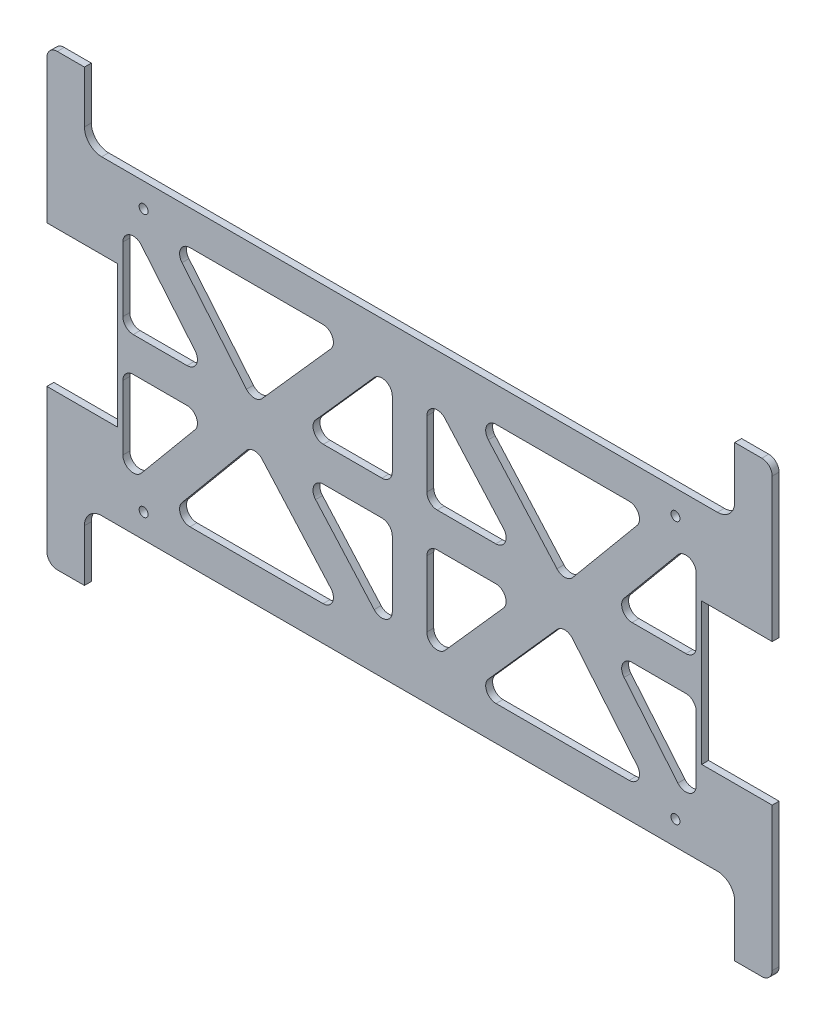
SolidWorks part; units mm, degrees
ref_plane "前视基准面" through (0, 0, 0) normal (0, 0, 1) x (1, 0, 0)
ref_plane "上视基准面" through (0, 0, 0) normal (0, 1, 0) x (1, 0, 0)
ref_plane "右视基准面" through (0, 0, 0) normal (1, 0, 0) x (0, 0, -1)
sketch "草图1" plane through (0, 0, 0) normal (0, 0, 1) x (1, 0, 0)
  line L0 (105, 90) -> (105, -49910) construction
  line L1 (7.8, 0) -> (202.2, 0)
  line L2 (0, 0) -> (0, 90)
  line L3 (7.8, 90) -> (202.2, 90)
  line L4 (210, 0) -> (210, 90)
  line L5 (0, 45) -> (210, 45) construction
  line L6 (10, 48.9878) -> (10, -49951.0122) construction
  line L7 (205.2, 93) -> (205.2, 110)
  line L8 (3, -20) -> (4.8, -20)
  line L9 (0, 90) -> (0, 107)
  line L10 (3, 110) -> (4.8, 110)
  line L11 (4.8, 93) -> (4.8, 110)
  line L12 (207, 110) -> (205.2, 110)
  line L13 (210, 90) -> (210, 107)
  line L14 (22, 71.7103) -> (22, 53)
  line L15 (207, -20) -> (205.2, -20)
  line L16 (210, 0) -> (210, -17)
  line L17 (205.2, -3) -> (205.2, -20)
  line L18 (4.8, -3) -> (4.8, -20)
  line L19 (0, 0) -> (0, -17)
  line L20 (25, 50) -> (40.5831, 50)
  line L21 (42.8883, 54.9199) -> (27.3052, 73.6302)
  line L22 (39.1117, 75.0801) -> (57.7672, 52.6808)
  line L23 (62.316, 52.6093) -> (82.1982, 75.0085)
  line L24 (79.9546, 80) -> (41.4169, 80)
  line L25 (100, 72.101) -> (100, 53)
  line L26 (97, 50) -> (80.0454, 50)
  line L27 (77.8018, 54.9915) -> (94.7564, 74.0925)
  line L28 (113, 50) -> (129.9546, 50)
  line L29 (110, 72.101) -> (110, 53)
  line L30 (132.1982, 54.9915) -> (115.2436, 74.0925)
  line L31 (147.684, 52.6093) -> (127.8018, 75.0085)
  line L32 (130.0454, 80) -> (168.5831, 80)
  line L33 (170.8883, 75.0801) -> (152.2328, 52.6808)
  line L34 (167.1117, 54.9199) -> (182.6948, 73.6302)
  line L35 (185, 50) -> (169.4169, 50)
  line L36 (188, 71.7103) -> (188, 53)
  line L37 (185, 40) -> (169.4169, 40)
  line L38 (188, 18.2897) -> (188, 37)
  line L39 (167.1117, 35.0801) -> (182.6948, 16.3698)
  line L40 (170.8883, 14.9199) -> (152.2328, 37.3192)
  line L41 (130.0454, 10) -> (168.5831, 10)
  line L42 (147.684, 37.3907) -> (127.8018, 14.9915)
  line L43 (113, 40) -> (129.9546, 40)
  line L44 (110, 17.899) -> (110, 37)
  line L45 (132.1982, 35.0085) -> (115.2436, 15.9075)
  line L46 (97, 40) -> (80.0454, 40)
  line L47 (100, 17.899) -> (100, 37)
  line L48 (77.8018, 35.0085) -> (94.7564, 15.9075)
  line L49 (62.316, 37.3907) -> (82.1982, 14.9915)
  line L50 (79.9546, 10) -> (41.4169, 10)
  line L51 (39.1117, 14.9199) -> (57.7672, 37.3192)
  line L52 (42.8883, 35.0801) -> (27.3052, 16.3698)
  line L53 (25, 40) -> (40.5831, 40)
  line L54 (22, 18.2897) -> (22, 37)
  circle A0 centre (2.5, 53) radius 1.75
  circle A1 centre (17.5, 53) radius 1.75
  circle A2 centre (17.5, 37) radius 1.75
  circle A3 centre (2.5, 37) radius 1.75
  circle A4 centre (207.5, 37) radius 1.75
  circle A5 centre (192.5, 37) radius 1.75
  circle A6 centre (192.5, 53) radius 1.75
  circle A7 centre (207.5, 53) radius 1.75
  arc A8 (205.2, 93) -> (202.2, 90) centre (202.2, 93) cw
  arc A9 (7.8, 90) -> (4.8, 93) centre (7.8, 93) cw
  arc A10 (4.8, -3) -> (7.8, 0) centre (7.8, -3) cw
  arc A11 (205.2, -3) -> (202.2, 0) centre (202.2, -3) ccw
  arc A12 (185, 50) -> (188, 53) centre (185, 53) ccw
  arc A13 (167.1117, 54.9199) -> (169.4169, 50) centre (169.4169, 53) ccw
  arc A14 (182.6948, 73.6302) -> (188, 71.7103) centre (185, 71.7103) cw
  arc A15 (168.5831, 80) -> (170.8883, 75.0801) centre (168.5831, 77) cw
  arc A16 (127.8018, 75.0085) -> (130.0454, 80) centre (130.0454, 77) cw
  arc A17 (113, 50) -> (110, 53) centre (113, 53) cw
  arc A18 (110, 72.101) -> (115.2436, 74.0925) centre (113, 72.101) cw
  arc A19 (129.9546, 50) -> (132.1982, 54.9915) centre (129.9546, 53) ccw
  arc A20 (169.4169, 40) -> (167.1117, 35.0801) centre (169.4169, 37) ccw
  arc A21 (185, 40) -> (188, 37) centre (185, 37) cw
  arc A22 (188, 18.2897) -> (182.6948, 16.3698) centre (185, 18.2897) cw
  arc A23 (170.8883, 14.9199) -> (168.5831, 10) centre (168.5831, 13) cw
  arc A24 (130.0454, 10) -> (127.8018, 14.9915) centre (130.0454, 13) cw
  arc A25 (152.2328, 37.3192) -> (147.684, 37.3907) centre (149.9276, 35.3992) ccw
  arc A26 (129.9546, 40) -> (132.1982, 35.0085) centre (129.9546, 37) cw
  arc A27 (113, 40) -> (110, 37) centre (113, 37) ccw
  arc A28 (110, 17.899) -> (115.2436, 15.9075) centre (113, 17.899) ccw
  arc A29 (82.1982, 14.9915) -> (79.9546, 10) centre (79.9546, 13) cw
  arc A30 (100, 17.899) -> (94.7564, 15.9075) centre (97, 17.899) cw
  arc A31 (80.0454, 40) -> (77.8018, 35.0085) centre (80.0454, 37) ccw
  arc A32 (97, 40) -> (100, 37) centre (97, 37) cw
  arc A33 (100, 53) -> (97, 50) centre (97, 53) cw
  arc A34 (100, 72.101) -> (94.7564, 74.0925) centre (97, 72.101) ccw
  arc A35 (80.0454, 50) -> (77.8018, 54.9915) centre (80.0454, 53) cw
  arc A36 (57.7672, 52.6808) -> (62.316, 52.6093) centre (60.0724, 54.6008) ccw
  arc A37 (62.316, 37.3907) -> (57.7672, 37.3192) centre (60.0724, 35.3992) ccw
  arc A38 (41.4169, 10) -> (39.1117, 14.9199) centre (41.4169, 13) cw
  arc A39 (27.3052, 16.3698) -> (22, 18.2897) centre (25, 18.2897) cw
  arc A40 (25, 40) -> (22, 37) centre (25, 37) ccw
  arc A41 (42.8883, 35.0801) -> (40.5831, 40) centre (40.5831, 37) ccw
  arc A42 (40.5831, 50) -> (42.8883, 54.9199) centre (40.5831, 53) ccw
  arc A43 (22, 53) -> (25, 50) centre (25, 53) ccw
  arc A44 (22, 71.7103) -> (27.3052, 73.6302) centre (25, 71.7103) cw
  arc A45 (39.1117, 75.0801) -> (41.4169, 80) centre (41.4169, 77) cw
  arc A46 (82.1982, 75.0085) -> (79.9546, 80) centre (79.9546, 77) ccw
  arc A47 (147.684, 52.6093) -> (152.2328, 52.6808) centre (149.9276, 54.6008) ccw
  arc A48 (207, 110) -> (210, 107) centre (207, 107) cw
  arc A49 (207, -20) -> (210, -17) centre (207, -17) ccw
  arc A50 (0, -17) -> (3, -20) centre (3, -17) ccw
  arc A51 (0, 107) -> (3, 110) centre (3, 107) cw
  circle A52 centre (28, 83) radius 1.3
  circle A53 centre (182, 83) radius 1.3
  circle A54 centre (182, 7) radius 1.3
  circle A55 centre (28, 7) radius 1.3
  point P7 (105, 90)
  point P8 (105, 0)
  point P81 (205.2, 90)
  point P84 (4.8, 90)
  point P87 (4.8, 0)
  point P90 (205.2, 0)
  point P93 (188, 50)
  point P96 (163.0141, 50)
  point P99 (188, 80)
  point P102 (174.9859, 80)
  point P105 (123.3712, 80)
  point P108 (110, 50)
  point P111 (110, 80)
  point P114 (136.6288, 50)
  point P117 (163.0141, 40)
  point P120 (188, 40)
  point P123 (188, 10)
  point P126 (174.9859, 10)
  point P129 (123.3712, 10)
  point P132 (150, 40)
  point P135 (136.6288, 40)
  point P138 (110, 40)
  point P141 (110, 10)
  point P144 (86.6288, 10)
  point P147 (100, 10)
  point P150 (73.3712, 40)
  point P153 (100, 40)
  point P156 (100, 50)
  point P159 (100, 80)
  point P162 (73.3712, 50)
  point P165 (60, 50)
  point P168 (60, 40)
  point P171 (35.0141, 10)
  point P174 (22, 10)
  point P177 (22, 40)
  point P180 (46.9859, 40)
  point P183 (46.9859, 50)
  point P186 (22, 50)
  point P189 (22, 80)
  point P192 (35.0141, 80)
  point P195 (86.6288, 80)
  point P196 (150, 50)
  point P199 (210, 110)
  point P202 (210, -20)
  point P205 (0, -20)
  point P208 (0, 110)
  dimension "D3" = 3.5
  dimension "D17" = 3
  dimension "D18" = 3
  dimension "D19" = 3
  dimension "D22" = 2.6
  dimension "D1" = 90
  dimension "D2" = 175
  dimension "D4" = 10
  dimension "D5" = 15
  dimension "D6" = 16
  dimension "D7" = 210
  dimension "D8" = 4.8
  dimension "D9" = 20
  dimension "D10" = 10
  dimension "D11" = 5
  dimension "D12" = 5
  dimension "D13" = 10
  dimension "D14" = 10
  dimension "D15" = 22
  dimension "D16" = 60
  dimension "D20" = 77
  dimension "D21" = 38
extrude "凸台-拉伸1" add sketch "草图1" along normal blind 2
sketch "草图2" plane through (0, 0, 2) normal (0, 0, 1) x (1, 0, 0)
  line L0 (0, 107) -> (0, -17) construction
  line L1 (0, 65.5) -> (20.4, 65.5)
  line L2 (0, 65.5) -> (0, 24.5)
  line L3 (0, 24.5) -> (20.4, 24.5)
  line L4 (20.4, 65.5) -> (20.4, 24.5)
  line L5 (210, 45) -> (171.9784, 45) construction
  line L7 (202.2, 90) -> (7.8, 90) construction
  line L8 (7.8, 0) -> (202.2, 0) construction
  line L9 (105, 90) -> (105, 0) construction
  line L10 (189.6, 65.5) -> (189.6, 24.5)
  line L11 (210, 24.5) -> (189.6, 24.5)
  line L12 (210, 65.5) -> (210, 24.5)
  line L13 (210, 65.5) -> (189.6, 65.5)
  dimension "D1" = 41
  dimension "D2" = 20.4
extrude "切除-拉伸1" cut sketch "草图2" against normal through all
sketch "草图3" plane through (0, 0, 2) normal (0, 0, 1) x (1, 0, 0)
  line L0 (202.2, 90) -> (7.8, 90) construction
  line L1 (4.8, 110) -> (10.8603, 110)
  line L2 (4.8, 110) -> (4.8, 90)
  line L3 (4.8, 90) -> (10.8603, 90)
  line L4 (10.8603, 110) -> (10.8603, 90)
  line L5 (105, 90) -> (105, 1.2463) construction
  line L6 (20.4, 45) -> (189.6, 45) construction
  line L7 (20.4, 24.5) -> (20.4, 65.5) construction
  line L8 (189.6, 65.5) -> (189.6, 24.5) construction
  line L9 (199.1397, 110) -> (199.1397, 90)
  line L10 (205.2, 90) -> (199.1397, 90)
  line L11 (205.2, 110) -> (205.2, 90)
  line L12 (205.2, 110) -> (199.1397, 110)
  line L13 (205.2, -20) -> (199.1397, -20)
  line L14 (205.2, -20) -> (205.2, 0)
  line L15 (205.2, 0) -> (199.1397, 0)
  line L16 (199.1397, -20) -> (199.1397, 0)
  line L17 (10.8603, -20) -> (10.8603, 0)
  line L18 (4.8, 0) -> (10.8603, 0)
  line L19 (4.8, -20) -> (4.8, 0)
  line L20 (4.8, -20) -> (10.8603, -20)
extrude "凸台-拉伸2" add sketch "草图3" against normal up to surface (2 mm away) up to face at (105, 45, 0)
fillet "圆角3" radius 5 1 edges at (10.8603, 0, 1)
fillet "圆角4" radius 5 1 edges at (199.1397, 0, 1)
fillet "圆角5" radius 5 1 edges at (199.1397, 90, 1)
fillet "圆角6" radius 5 1 edges at (10.8603, 90, 1)
